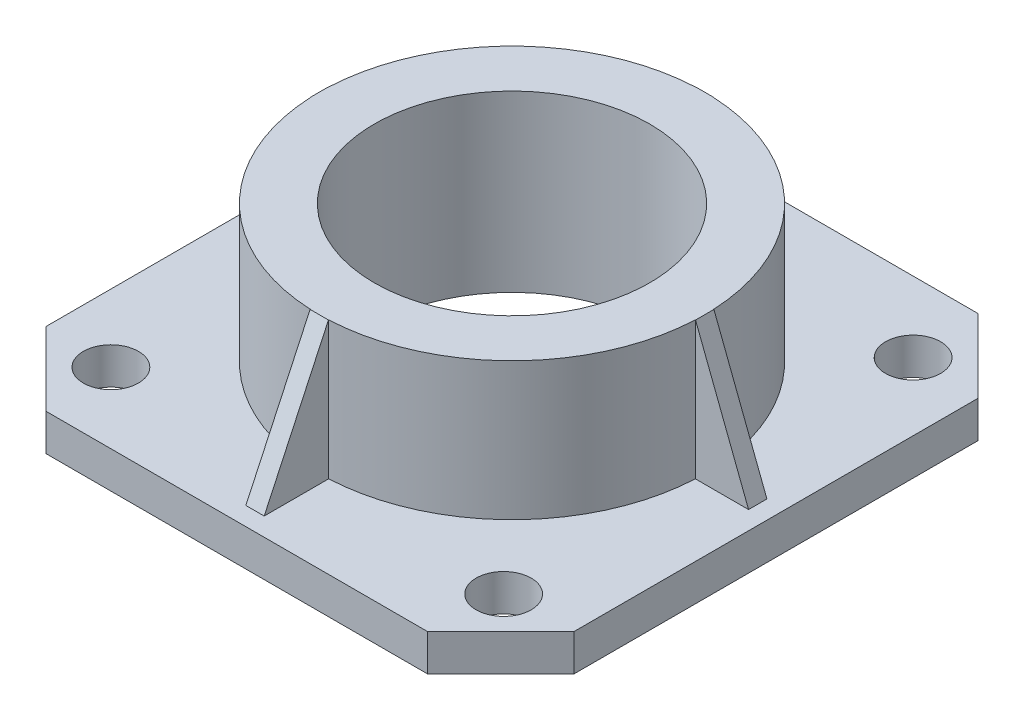
SolidWorks part; units mm, degrees
ref_plane "Front Plane" through (0, 0, 0) normal (0, 0, 1) x (1, 0, 0)
ref_plane "Top Plane" through (0, 0, 0) normal (0, 1, 0) x (1, 0, 0)
ref_plane "Right Plane" through (0, 0, 0) normal (1, 0, 0) x (0, 0, -1)
sketch "Sketch1" plane through (0, 0, 0) normal (0, 1, 0) x (1, 0, 0)
  line L0 (-14.3876, 11) -> (-10.3876, 15)
  line L1 (-10.3876, -15) -> (10.3876, -15)
  line L2 (-14.3876, -11) -> (-14.3876, 11)
  line L3 (-10.3876, 15) -> (10.3876, 15)
  line L4 (14.3876, -11) -> (14.3876, 11)
  line L5 (-14.3876, -15) -> (14.3876, 15) construction
  line L6 (-14.3876, 15) -> (14.3876, -15) construction
  line L7 (10.3876, 15) -> (14.3876, 11)
  line L8 (10.3876, -15) -> (14.3876, -11)
  line L9 (-14.3876, -11) -> (-10.3876, -15)
  circle A0 centre (0, 0) radius 7.5
  circle A1 centre (-10.6984, -11.1537) radius 1.5
  circle A2 centre (-10.6984, 11.1537) radius 1.5
  circle A3 centre (10.6984, 11.1537) radius 1.5
  circle A4 centre (10.6984, -11.1537) radius 1.5
  point P0 (0, 0)
  dimension "D2" = 3
  dimension "D1" = 30
  dimension "D3" = 2.5
extrude "Boss-Extrude1" add sketch "Sketch1" along normal blind 2
sketch "Sketch2" plane through (0, 2, 0) normal (0, 1, 0) x (1, 0, 0)
  circle A0 centre (0, 0) radius 7.5
  circle A1 centre (0, 0) radius 10.5
  circle A2 centre (0, 0) radius 7.5 construction
  dimension "D1" = 3
extrude "Boss-Extrude2" add sketch "Sketch2" along normal blind 7.5
sketch "Sketch4" plane through (0, 0, 0) normal (1, 0, 0) x (0, 0, -1)
  line L0 (10.5, 9.5) -> (14, 2)
  line L1 (14, 2) -> (7.5, 2)
  line L2 (-10.5, 9.5) -> (-7.5, 9.5)
  line L3 (-7.5, 9.5) -> (-7.5, 2)
  line L4 (-7.5, 2) -> (-14, 2)
  line L5 (-11, 2) -> (-15, 2) construction
  line L6 (-14, 2) -> (-10.5, 9.5)
  line L7 (10.5, 9.5) -> (7.5, 9.5)
  line L8 (7.5, 9.5) -> (7.5, 2)
  dimension "D1" = 1
  dimension "D2" = 1
extrude "Boss-Extrude4" add sketch "Sketch4" along normal blind 0.5 and the other way blind 0.5
sketch "Sketch5" plane through (0, 0, 0) normal (0, 0, 1) x (1, 0, 0)
  line L0 (-10.5, 9.5) -> (-13.3876, 2)
  line L1 (-14.3876, 2) -> (-10.3876, 2) construction
  line L2 (-13.3876, 2) -> (-7.5, 2)
  line L3 (-10.3876, 2) -> (10.3876, 2) construction
  line L4 (-7.5, 2) -> (-7.5, 9.5)
  line L5 (-7.5, 9.5) -> (-10.5, 9.5)
  line L6 (10.5, 9.5) -> (13.3876, 2)
  line L7 (10.5, 9.5) -> (0.5, 9.5) construction
  line L8 (10.3876, 2) -> (14.3876, 2) construction
  line L9 (13.3876, 2) -> (7.5, 2)
  line L10 (7.5, 2) -> (7.5, 9.5)
  line L11 (7.5, 9.5) -> (10.5, 9.5)
  dimension "D1" = 1
  dimension "D2" = 1
extrude "Boss-Extrude5" add sketch "Sketch5" along normal blind 0.5 and the other way blind 0.5
